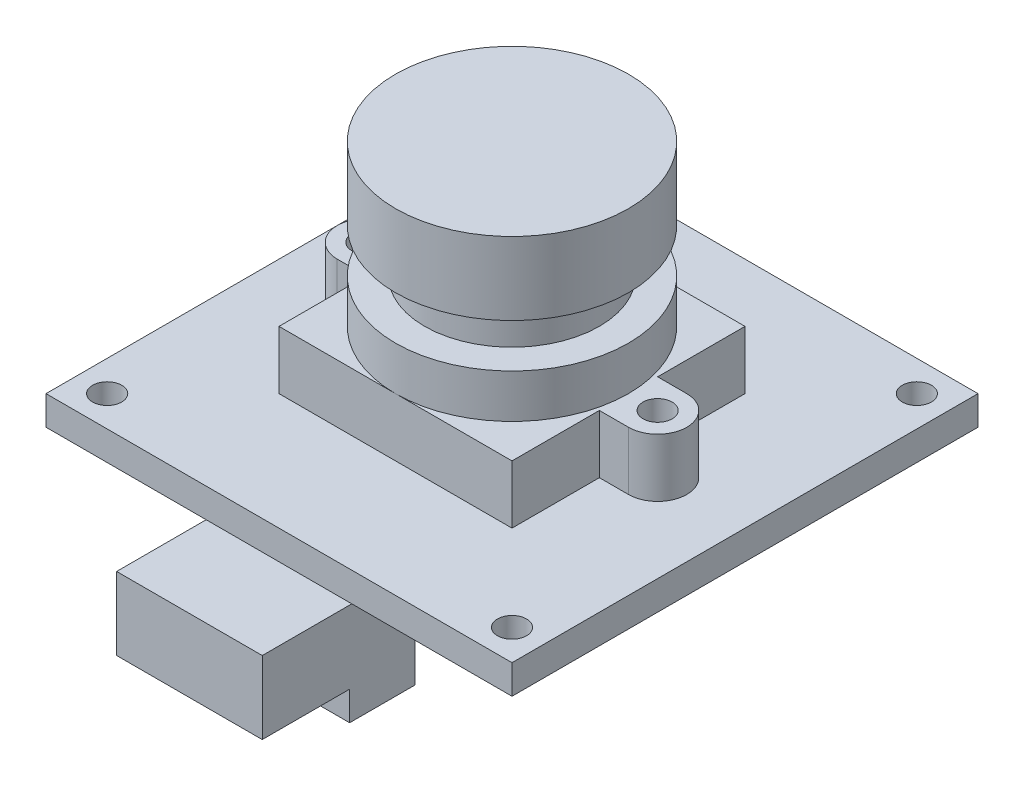
SolidWorks part; units mm, degrees
ref_plane "Front Plane" through (0, 0, 0) normal (0, 0, 1) x (1, 0, 0)
ref_plane "Top Plane" through (0, 0, 0) normal (0, 1, 0) x (1, 0, 0)
ref_plane "Right Plane" through (0, 0, 0) normal (1, 0, 0) x (0, 0, -1)
sketch "Sketch1" plane through (0, 0, 0) normal (0, 1, 0) x (1, 0, 0)
  line L0 (13.9, -13.9) -> (-13.9, 13.9) construction
  line L1 (-16, -16) -> (16, -16)
  line L2 (-16, -16) -> (-16, 16)
  line L3 (-16, -16) -> (16, 16) construction
  line L4 (16, -16) -> (16, 16)
  line L45 (-16, 16) -> (16, 16)
  circle A0 centre (-13.9, 13.9) radius 1
  circle A1 centre (13.9, 13.9) radius 1
  circle A2 centre (-13.9, -13.9) radius 1
  circle A3 centre (13.9, -13.9) radius 1
  point P3 (0, 0)
  point P11 (0, 0)
  point P38 (-16, 0)
  point P45 (17.9444, 0)
  point P46 (16, 0)
  dimension "D8" = 2
  dimension "D4" = 27.8
  dimension "D5" = 27.8
  dimension "D11" = 32
extrude "Boss-Extrude1" add sketch "Sketch1" along normal blind 2
sketch "Sketch2" plane through (0, 2, 0) normal (0, 1, 0) x (1, 0, 0)
  line L0 (10, 0) -> (9, 0) construction
  line L1 (-8, -8) -> (8, -8)
  line L2 (-8, -8) -> (-8, -2)
  line L3 (-8, 8) -> (8, 8)
  line L4 (8, -8) -> (8, -2)
  line L7 (10, -2) -> (8, -2)
  line L8 (10, 2) -> (8, 2)
  line L9 (-8, 2) -> (-8, 8)
  line L10 (-9, 0) -> (-10, 0) construction
  line L13 (8, 2) -> (8, 8)
  line L14 (-8, 2) -> (-10, 2)
  line L15 (-8, -2) -> (-10, -2)
  arc A0 (10, -2) -> (10, 2) centre (10, 0) ccw
  arc A1 (-10, 2) -> (-10, -2) centre (-10, 0) ccw
  circle A2 centre (10, 0) radius 1
  circle A3 centre (-10, 0) radius 1
  point P0 (0, 0)
  point P8 (0, 0)
  dimension "D4" = 2
  dimension "D1" = 16
  dimension "D2" = 20
  dimension "D3" = 4
extrude "Boss-Extrude2" add sketch "Sketch2" along normal blind 4
sketch "Sketch3" plane through (0, 6, 0) normal (0, 1, 0) x (1, 0, 0)
  circle A0 centre (0, 0) radius 8
  dimension "D1" = 16
extrude "Boss-Extrude3" add sketch "Sketch3" along normal blind 3
sketch "Sketch4" plane through (0, 9, 0) normal (0, 1, 0) x (1, 0, 0)
  circle A0 centre (0, 0) radius 6
  dimension "D1" = 12
extrude "Boss-Extrude4" add sketch "Sketch4" along normal blind 3
sketch "Sketch5" plane through (0, 12, 0) normal (0, 1, 0) x (1, 0, 0)
  circle A0 centre (0, 0) radius 8
extrude "Boss-Extrude5" add sketch "Sketch5" along normal blind 5
sketch "草图1" plane through (0, 0, 0) normal (0, -1, 0) x (1, 0, 0)
  line L1 (-5, 16.15) -> (5, 16.15)
  line L2 (-5, 16.15) -> (-5, 11.65)
  line L3 (-5, 11.65) -> (5, 11.65)
  line L4 (5, 16.15) -> (5, 11.65)
  circle A0 centre (13.9, 13.9) radius 1 construction
  circle A1 centre (13.9, 13.9) radius 1 construction
  point P4 (0, 16.15)
  point P11 (-5, 13.9)
  dimension "D1" = 4.5
  dimension "D2" = 10
extrude "凸台-拉伸1" add sketch "草图1" along normal blind 7
sketch "草图2" plane through (0, 0, 16.15) normal (0, 0, 1) x (1, 0, 0)
  line L0 (5, -7) -> (5, 0) construction
  line L1 (-5, 0) -> (5, 0)
  line L2 (-5, 0) -> (-5, -5)
  line L3 (-5, -5) -> (5, -5)
  line L4 (5, 0) -> (5, -5)
  line L5 (5, 0) -> (16, 0) construction
  dimension "D1" = 5
  dimension "D2" = 10
extrude "凸台-拉伸2" add sketch "草图2" along normal blind 6
